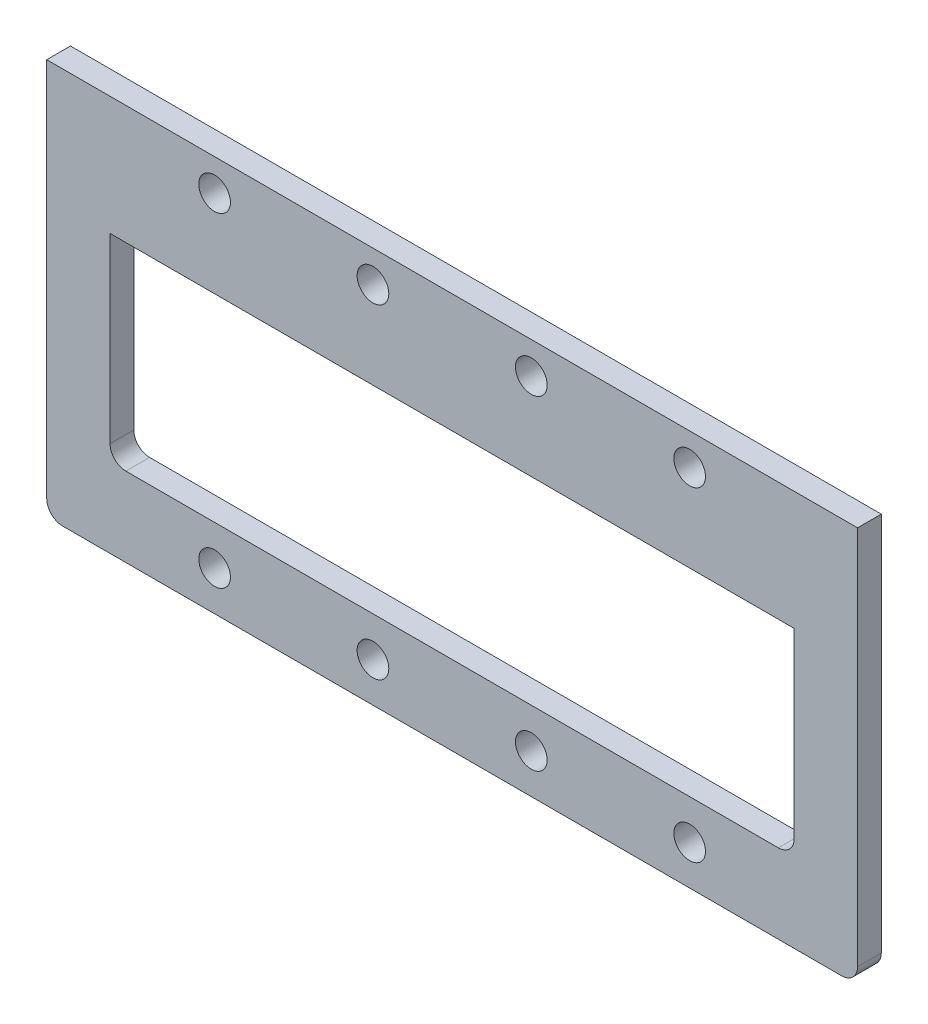
SolidWorks part; units mm, degrees
ref_plane "Front Plane" through (0, 0, 0) normal (0, 0, 1) x (1, 0, 0)
ref_plane "Top Plane" through (0, 0, 0) normal (0, 1, 0) x (1, 0, 0)
ref_plane "Right Plane" through (0, 0, 0) normal (1, 0, 0) x (0, 0, -1)
sketch "Sketch1" plane through (0, 0, 0) normal (0, 0, 1) x (1, 0, 0)
  line L0 (-42.6363, 9.1545) -> (-42.6363, -15.8455)
  line L1 (43.7637, 9.1545) -> (-42.6363, 9.1545)
  line L2 (43.7637, -15.8455) -> (43.7637, 9.1545)
  line L3 (-42.6363, -15.8455) -> (43.7637, -15.8455)
  line L4 (-50.6363, 24.1545) -> (-50.6363, 18.1545)
  line L5 (-50.6363, 18.1545) -> (-50.6363, 16.1545)
  line L6 (-50.6363, 16.1545) -> (-50.6363, -25.8455)
  line L7 (-50.6363, -25.8455) -> (51.7637, -25.8455)
  line L8 (51.7637, -25.8455) -> (51.7637, 16.1545)
  line L9 (51.7637, 16.1545) -> (51.7637, 18.1545)
  line L10 (51.7637, 18.1545) -> (51.7637, 24.1545)
  line L11 (51.7637, 24.1545) -> (-50.6363, 24.1545)
extrude "Boss-Extrude1" add sketch "Sketch1" along normal blind 3
sketch "Sketch2" plane through (0, 0, 3) normal (0, 0, 1) x (1, 0, 0)
  line L0 (-50.6363, 20.1545) -> (51.7637, 20.1545) construction
  line L1 (-35.5881, 24.1545) -> (-35.5881, 9.1545) construction
  line L2 (51.7637, 24.1545) -> (-50.6363, 24.1545) construction
  line L3 (43.7637, 9.1545) -> (-42.6363, 9.1545) construction
  line L4 (-35.5881, -15.8455) -> (-35.5881, -25.8455) construction
  line L5 (-42.6363, -15.8455) -> (43.7637, -15.8455) construction
  line L6 (-50.6363, -25.8455) -> (51.7637, -25.8455) construction
  line L7 (0.5637, -20.8455) -> (0.5637, 20.1545) construction
  line L9 (-50.6363, 24.1545) -> (-50.6363, -25.8455) construction
  line L10 (51.7637, -25.8455) -> (51.7637, 24.1545) construction
  line L11 (-50.6363, -20.8455) -> (51.7637, -20.8455) construction
  circle A0 centre (-29.4363, 20.1545) radius 2
  circle A1 centre (-29.4363, -20.8455) radius 2
  circle A2 centre (-9.4363, -20.8455) radius 2
  circle A3 centre (-9.4363, 20.1545) radius 2
  circle A4 centre (10.5637, -20.8455) radius 2
  circle A5 centre (10.5637, 20.1545) radius 2
  circle A6 centre (30.5637, -20.8455) radius 2
  circle A7 centre (30.5637, 20.1545) radius 2
  point P41 (-35.5881, -20.8455)
  dimension "D2" = 30
  dimension "D3" = 4
  dimension "D4" = 4
  dimension "D6" = 4
  dimension "D1" = 4
  dimension "D5" = 20
extrude "Cut-Extrude2" cut sketch "Sketch2" against normal through all both and the other way through all
fillet "Fillet1" radius 2 4 edges at (43.7637, -15.8455, 1.5) (-42.6363, -15.8455, 1.5) (-50.6363, -25.8455, 1.5) (51.7637, -25.8455, 1.5)
